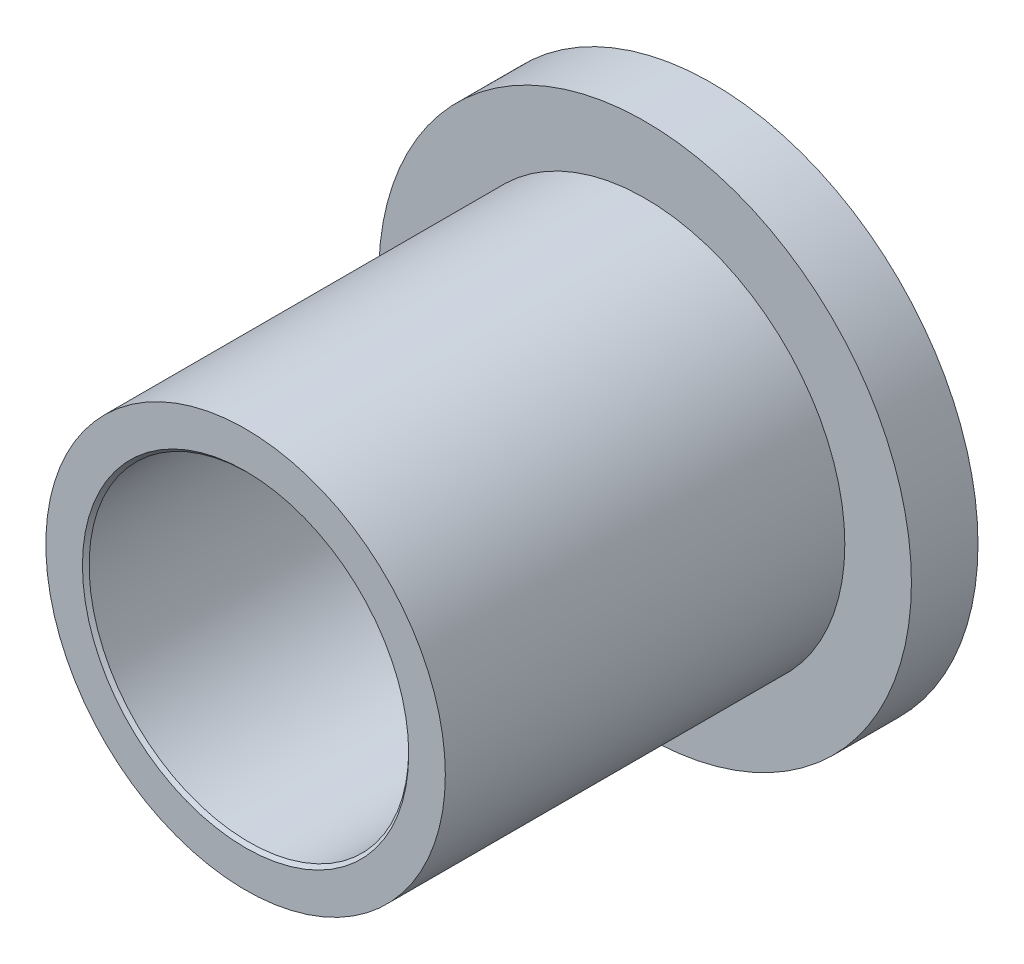
SolidWorks part; units mm, degrees
ref_plane "前视基准面" through (0, 0, 0) normal (0, 0, 1) x (1, 0, 0)
ref_plane "上视基准面" through (0, 0, 0) normal (0, 1, 0) x (1, 0, 0)
ref_plane "右视基准面" through (0, 0, 0) normal (1, 0, 0) x (0, 0, -1)
sketch "草图1" plane through (0, 0, 0) normal (0, 0, 1) x (1, 0, 0)
  circle A0 centre (0, 0) radius 2
  dimension "D1" = 4
extrude "凸台-拉伸1" add sketch "草图1" along normal blind 0.5 contours A0
sketch "草图2" plane through (0, 0, 0.5) normal (0, 0, 1) x (1, 0, 0)
  circle A0 centre (0, 0) radius 1.5
  dimension "D1" = 3
extrude "凸台-拉伸2" add sketch "草图2" along normal blind 3
hole_wizard "M2 间隙孔1" positions "草图3" profile "草图4" hole size "M2" standard "GB" end condition through all
sketch "草图3" plane through (0, 0, 3.5) normal (0, 0, 1) x (1, 0, 0)
  point P0 (0, 0)
  point P4 (0, 0)
sketch "草图4" plane through (0, 0, 3.5) normal (1, 0, 0) x (0, -1, 0)
  line L0 (0, 0) -> (0, 3.5)
  line L1 (0, 3.5) -> (1.2, 3.5)
  line L2 (1.2, 3.5) -> (1.2, 0.025)
  line L3 (1.2, 0.025) -> (1.225, 0)
  line L5 (1.225, 0) -> (0, 0)
  line L6 (-1.2, 0.025) -> (-1.225, 0) construction
  line L11 (0, -6.35) -> (0, 107.95) construction
  dimension "通孔孔直径" = 2.4
  dimension "通孔孔深度" = 3.5
  dimension "近端锥形沉头孔直径" = 2.45
  dimension "近端锥形沉头孔角度" = 90
